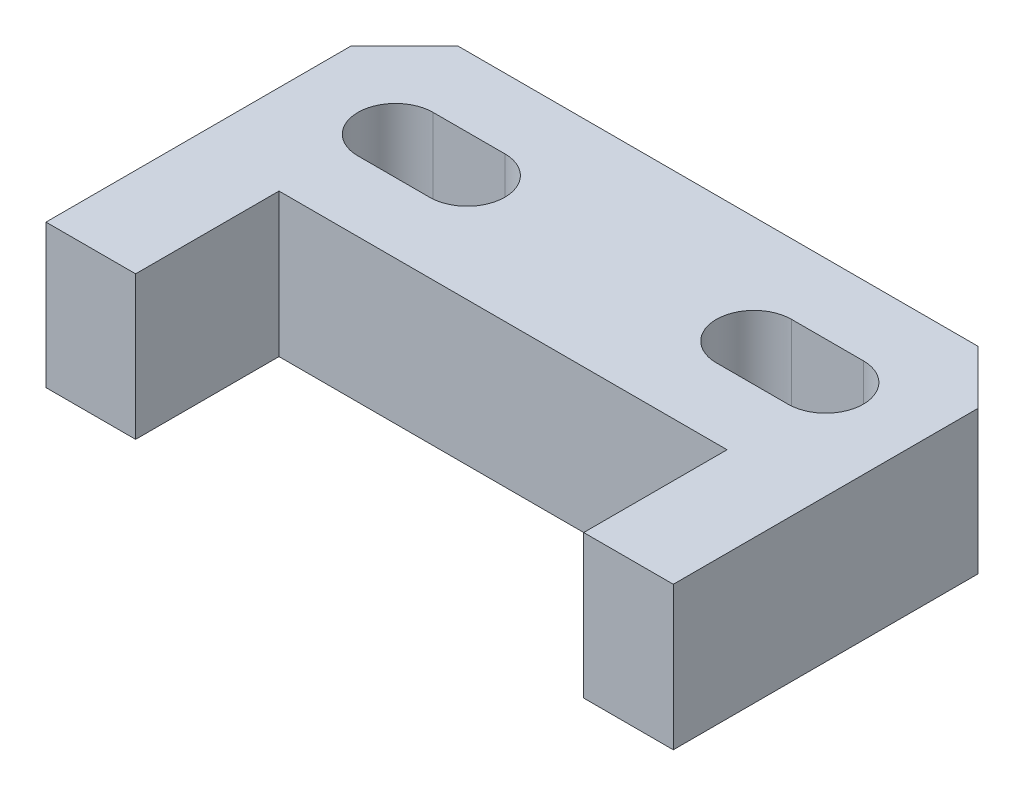
SolidWorks part; units mm, degrees
ref_plane "정면" through (0, 0, 0) normal (0, 0, 1) x (1, 0, 0)
ref_plane "윗면" through (0, 0, 0) normal (0, 1, 0) x (1, 0, 0)
ref_plane "우측면" through (0, 0, 0) normal (1, 0, 0) x (0, 0, -1)
sketch "스케치1" plane through (0, 0, 0) normal (0, 1, 0) x (1, 0, 0)
  line L0 (0, 0) -> (0, 20)
  line L1 (0, 20) -> (35, 20)
  line L2 (35, 20) -> (35, 0)
  line L3 (35, 0) -> (30, 0)
  line L4 (30, 0) -> (30, 8)
  line L5 (30, 8) -> (5, 8)
  line L6 (5, 8) -> (5, 0)
  line L7 (5, 0) -> (0, 0)
  dimension "D1" = 5
  dimension "D2" = 8
  dimension "D3" = 25
  dimension "D4" = 20
extrude "보스-돌출1" add sketch "스케치1" along normal blind 8
sketch "스케치2" plane through (0, 8, 0) normal (0, 1, 0) x (1, 0, 0)
  line L0 (7.5, 14) -> (27.5, 14) construction
  line L1 (27.5, 14) -> (35, 14) construction
  line L2 (35, 0) -> (35, 20) construction
  line L3 (0, 14) -> (7.5, 14) construction
  line L4 (0, 20) -> (0, 0) construction
  line L5 (29.5, 14) -> (25.5, 14) construction
  line L6 (29.5, 11.9) -> (25.5, 11.9)
  line L7 (29.5, 16.1) -> (25.5, 16.1)
  line L8 (5.5, 14) -> (9.5, 14) construction
  line L9 (5.5, 16.1) -> (9.5, 16.1)
  line L10 (5.5, 11.9) -> (9.5, 11.9)
  line L11 (17.5, 14) -> (17.5, 8) construction
  line L12 (5, 8) -> (30, 8) construction
  line L13 (17.5, 14) -> (17.5, 20) construction
  line L14 (35, 20) -> (0, 20) construction
  arc A0 (29.5, 11.9) -> (29.5, 16.1) centre (29.5, 14) ccw
  arc A1 (25.5, 16.1) -> (25.5, 11.9) centre (25.5, 14) ccw
  arc A2 (5.5, 16.1) -> (5.5, 11.9) centre (5.5, 14) ccw
  arc A3 (9.5, 11.9) -> (9.5, 16.1) centre (9.5, 14) ccw
  point P10 (27.5, 14)
  point P16 (7.5, 14)
  dimension "D1" = 2.1
  dimension "D2" = 4
  dimension "D3" = 20
extrude "컷-돌출1" cut sketch "스케치2" against normal blind 8
chamfer "모따기1" distance 3 angle 45 2 edges at (35, 4, -20) (0, 4, -20)
